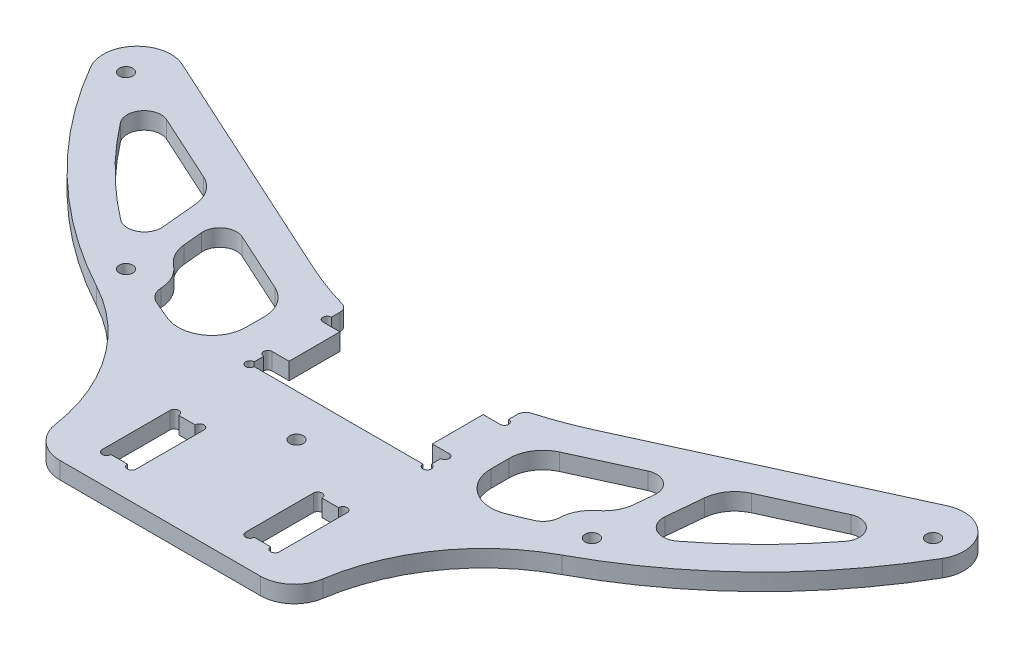
SolidWorks part; units mm, degrees
material "Custom Plastic"
ref_plane "Front" through (0, 0, 0) normal (0, 0, 1) x (1, 0, 0)
ref_plane "Top" through (0, 0, 0) normal (0, 1, 0) x (1, 0, 0)
ref_plane "Right" through (0, 0, 0) normal (1, 0, 0) x (0, 0, -1)
sketch "Sketch1" plane through (0, 0, 0) normal (0, 1, 0) x (1, 0, 0)
  line L0 (33.1787, -158.75) -> (33.1787, -153.6488)
  line L9 (52.8053, -115.5015) -> (143.1995, -74.1748)
  line L10 (-33.1787, -158.75) -> (-33.1787, -153.6488)
  line L11 (151.1214, -87.25) -> (159.4786, -92.075) construction
  line L14 (-49.275, -225.5484) -> (-49.275, -177.435) construction
  line L15 (-36.575, -225.5484) -> (-36.575, -169.0294) construction
  line L16 (49.275, -177.435) -> (49.275, -225.5484) construction
  line L17 (49.275, -225.5484) -> (-49.275, -225.5484)
  line L18 (-30.225, -225.5484) -> (-36.575, -225.5484) construction
  line L19 (33.1787, -141.2831) -> (33.1787, -130.3903) construction
  line L20 (-33.1788, -137.2542) -> (-33.1788, -142.0167) construction
  line L21 (26.8287, -137.2542) -> (26.8287, -142.0167) construction
  line L22 (-33.1787, -131.4238) -> (-26.8287, -131.4238)
  line L24 (-33.1787, -150.4738) -> (-26.8287, -150.4738)
  line L25 (-26.8287, -131.4238) -> (-26.8287, -150.4738)
  line L26 (33.1787, -131.4238) -> (26.8287, -131.4238)
  line L28 (33.1787, -150.4738) -> (26.8287, -150.4738)
  line L29 (26.8287, -131.4238) -> (26.8287, -150.4738)
  line L31 (-33.1787, -128.2488) -> (-33.1787, -122.5894)
  line L32 (33.1787, -128.2488) -> (33.1787, -122.5894)
  line L33 (-52.8053, -115.5015) -> (-143.1995, -74.1748)
  line L35 (-33.1787, -158.75) -> (33.1787, -158.75)
  circle A1 centre (-33.1787, -140.9488) radius 17.8012 construction
  circle A2 centre (151.1214, -87.25) radius 3.9624 construction
  arc A3 (-159.4786, -92.075) -> (-87.1399, -162.2278) centre (0, 0) ccw
  arc A5 (33.1787, -122.5894) -> (52.8053, -115.5015) centre (0, 0) ccw
  arc A6 (-52.8053, -115.5015) -> (-33.1787, -122.5894) centre (0, 0) ccw
  arc A7 (87.1399, -162.2278) -> (159.4786, -92.075) centre (0, 0) ccw
  circle A14 centre (151.1214, -87.25) radius 9.65 construction
  arc A15 (87.1399, -162.2278) -> (49.275, -225.5484) centre (121.1522, -225.5484) ccw
  arc A16 (159.4786, -92.075) -> (143.1995, -74.1748) centre (148.4801, -85.725) ccw
  arc A17 (-49.275, -225.5484) -> (-87.1399, -162.2278) centre (-121.1522, -225.5484) ccw
  arc A18 (-143.1995, -74.1748) -> (-159.4786, -92.075) centre (-148.4801, -85.725) ccw
  arc A19 (33.1787, -153.6488) -> (33.1787, -150.4738) centre (33.1787, -152.0613) ccw
  arc A20 (33.1787, -131.4238) -> (33.1787, -128.2488) centre (33.1787, -129.8363) ccw
  arc A21 (-33.1787, -128.2488) -> (-33.1787, -131.4238) centre (-33.1787, -129.8363) ccw
  arc A22 (-33.1787, -150.4738) -> (-33.1787, -153.6488) centre (-33.1787, -152.0613) ccw
  point P0 (0, 0)
  point P21 (-26.8287, -140.9488)
  dimension "D1" = 19.05
  dimension "D3" = 3.175
  dimension "D4" = 184.15
  dimension "D5" = 127
  dimension "D6" = 25.4
  dimension "D7" = 158.75
  dimension "D8" = 3.175
  dimension "D2" = 12.7
extrude "Boss-Extrude1" add sketch "Sketch1" along normal blind 6.35 contours A7 A16 L9 A5 L32 A20 L26 L29 L28 A19 L0 L35 L10 A22 L24 L25 L22 A21 L31 A6 L33 A18 A3 A17 L17 A15
fillet "Fillet4" radius 3.175 2 edges at (33.1787, 3.175, 122.5894) (-33.1787, 3.175, 122.5894)
hole_wizard "#10 Clearance Hole1" positions "Sketch2" profile "Sketch3" hole size "#10" standard "ANSI Inch" end condition through all
sketch "Sketch2" plane through (0, 6.35, 0) normal (0, 1, 0) x (1, 0, 0)
  circle A0 centre (-87.25, -151.1214) radius 3.7211 construction
  circle A1 centre (-151.1214, -87.25) radius 3.7211 construction
  circle A2 centre (87.25, -151.1214) radius 3.9624 construction
  circle A3 centre (0, -174.5) radius 3.7211 construction
  circle A4 centre (151.1214, -87.25) radius 3.9624 construction
  point P0 (-151.1214, -87.25)
  point P3 (-87.25, -151.1214)
  point P7 (87.25, -151.1214)
  point P10 (151.1214, -87.25)
  point P24 (0, -174.5)
sketch "Sketch3" plane through (-151.1214, 6.35, 87.25) normal (1, 0, 0) x (0, 0, 1)
  line L0 (0, 0) -> (0, 6.35)
  line L1 (0, 6.35) -> (2.5527, 6.35)
  line L2 (2.5527, 6.35) -> (2.5527, 0)
  line L5 (2.5527, 0) -> (0, 0)
  line L11 (0, -6.35) -> (0, 107.95) construction
  dimension "Thru Hole Dia." = 5.1054
  dimension "Thru Hole Depth" = 6.35
sketch "Sketch4" plane through (0, 6.35, 0) normal (0, 1, 0) x (1, 0, 0)
  line L0 (-26.8288, -214.084) -> (-33.1788, -214.084) construction
  line L1 (-23.7548, -214.084) -> (-29.9027, -214.084)
  line L2 (-20.4788, -214.084) -> (-20.4788, -188.684)
  line L3 (-23.7548, -188.684) -> (-29.9027, -188.684)
  line L4 (-33.1788, -214.084) -> (-33.1788, -188.684)
  line L5 (-26.8288, -188.684) -> (-33.1788, -188.684) construction
  line L7 (-33.1788, -137.2542) -> (-33.1788, -142.0167) construction
  line L9 (0, -227.8) -> (0, -127.8) construction
  line L10 (23.7548, -214.084) -> (29.9027, -214.084)
  line L11 (33.1787, -214.084) -> (33.1787, -188.684)
  line L12 (23.7548, -188.684) -> (29.9027, -188.684)
  line L13 (20.4787, -214.084) -> (20.4787, -188.684)
  arc A0 (-33.1788, -214.084) -> (-29.9027, -214.084) centre (-31.5407, -214.084) ccw
  arc A1 (-29.9027, -188.684) -> (-33.1788, -188.684) centre (-31.5407, -188.684) ccw
  arc A2 (-23.7548, -214.084) -> (-20.4788, -214.084) centre (-22.1168, -214.084) ccw
  arc A3 (-20.4788, -188.684) -> (-23.7548, -188.684) centre (-22.1168, -188.684) ccw
  arc A4 (23.7548, -214.084) -> (20.4787, -214.084) centre (22.1168, -214.084) cw
  arc A5 (33.1787, -214.084) -> (29.9027, -214.084) centre (31.5407, -214.084) cw
  arc A6 (29.9027, -188.684) -> (33.1787, -188.684) centre (31.5407, -188.684) cw
  arc A7 (20.4787, -188.684) -> (23.7548, -188.684) centre (22.1168, -188.684) cw
  dimension "D1" = 3.2761
  dimension "D3" = 12.7
extrude "Cut-Extrude1" cut sketch "Sketch4" against normal through all
fillet "Fillet5" radius 12.7 2 edges at (49.275, 3.175, 225.5484) (-49.275, 3.175, 225.5484)
sketch "Sketch5" plane through (0, 6.35, 0) normal (0, 1, 0) x (1, 0, 0)
  circle A0 centre (33.1787, -158.75) radius 1.5875
  circle A1 centre (-33.1787, -158.75) radius 1.5875
  dimension "D1" = 3.175
extrude "Cut-Extrude2" cut sketch "Sketch5" against normal through all
sketch "Sketch6" plane through (0, 6.35, 0) normal (0, 1, 0) x (1, 0, 0)
  line L0 (-128.1049, -95.0402) -> (-102.6375, -106.6834)
  line L1 (-33.1787, -157.1625) -> (-33.1787, -153.6488) construction
  line L2 (0, 0) -> (0, -69.1507) construction
  line L3 (-52.8053, -115.5015) -> (-143.1995, -74.1748) construction
  line L4 (94.5133, -125.0437) -> (84.9453, -125.0437) construction
  line L5 (88.452, -138.4784) -> (90.9676, -112.0187) construction
  line L6 (75.9635, -118.8783) -> (53.2982, -129.2405)
  line L7 (93.9917, -130.5298) -> (95.275, -117.0316)
  line L8 (84.9253, -125.2544) -> (84.2546, -132.3084)
  line L9 (45.8788, -140.7906) -> (45.8788, -147.5469)
  line L10 (128.1049, -95.0402) -> (102.6375, -106.6834)
  line L18 (-88.452, -138.4784) -> (-90.9676, -112.0187) construction
  line L19 (-45.8787, -140.7906) -> (-45.8787, -147.5469)
  line L20 (-84.9253, -125.2544) -> (-84.2546, -132.3084)
  line L21 (-93.9917, -130.5298) -> (-95.275, -117.0316)
  line L22 (-94.5133, -125.0437) -> (-84.9453, -125.0437) construction
  line L23 (-75.9635, -118.8783) -> (-53.2982, -129.2405)
  arc A0 (-104.1714, -136.1743) -> (-93.9917, -130.5298) centre (-100.3132, -131.1308) ccw
  circle A1 centre (-151.1214, -87.25) radius 12.7 construction
  arc A2 (-74.5605, -150.6061) -> (-79.4308, -141.1139) centre (-87.25, -151.1214) ccw
  arc A5 (-128.1049, -95.0402) -> (-135.7738, -104.6928) centre (-130.7452, -100.8152) ccw
  arc A6 (-84.2546, -132.3084) -> (-79.4308, -141.1139) centre (-71.6116, -131.1064) ccw
  arc A7 (-95.275, -117.0316) -> (-102.6375, -106.6834) centre (-107.918, -118.2336) ccw
  arc A8 (-70.8394, -156.131) -> (-74.5605, -150.6061) centre (-68.2157, -150.3484) cw
  arc A9 (-75.9635, -118.8783) -> (-84.9253, -125.2544) centre (-78.6038, -124.6534) ccw
  arc A10 (45.8788, -147.5469) -> (63.2651, -159.3507) centre (58.5788, -147.5469) ccw
  arc A11 (45.8788, -140.7906) -> (53.2982, -129.2405) centre (58.5788, -140.7906) cw
  arc A12 (70.8394, -156.131) -> (63.2651, -159.3507) centre (0, 0) cw
  arc A13 (135.7738, -104.6928) -> (104.1714, -136.1743) centre (0, 0) cw
  arc A14 (75.9635, -118.8783) -> (84.9253, -125.2544) centre (78.6038, -124.6534) cw
  arc A15 (70.8394, -156.131) -> (74.5605, -150.6061) centre (68.2157, -150.3484) ccw
  arc A16 (95.275, -117.0316) -> (102.6375, -106.6834) centre (107.918, -118.2336) cw
  arc A17 (84.2546, -132.3084) -> (79.4308, -141.1139) centre (71.6116, -131.1064) cw
  arc A18 (128.1049, -95.0402) -> (135.7738, -104.6928) centre (130.7452, -100.8152) cw
  arc A19 (74.5605, -150.6061) -> (79.4308, -141.1139) centre (87.25, -151.1214) cw
  arc A20 (104.1714, -136.1743) -> (93.9917, -130.5298) centre (100.3132, -131.1308) cw
  arc A23 (-135.7738, -104.6928) -> (-104.1714, -136.1743) centre (0, 0) ccw
  arc A24 (-159.4786, -92.075) -> (-87.1399, -162.2278) centre (0, 0) ccw construction
  arc A25 (-70.8394, -156.131) -> (-63.265, -159.3507) centre (0, 0) ccw
  arc A26 (-45.8787, -140.7906) -> (-53.2982, -129.2405) centre (-58.5787, -140.7906) ccw
  arc A27 (-45.8787, -147.5469) -> (-63.265, -159.3507) centre (-58.5787, -147.5469) cw
  point P34 (-89.7293, -125.0437)
  dimension "D1" = 25.4
  dimension "D3" = 12.7
  dimension "D5" = 12.7
  dimension "D8" = 12.7
  dimension "D9" = 12.7
  dimension "D10" = 12.7
  dimension "D11" = 6.35
  dimension "D2" = 12.7
  dimension "D4" = 12.7
  dimension "D6" = 60
  dimension "D7" = 9.525
extrude "Cut-Extrude3" cut sketch "Sketch6" against normal through all
